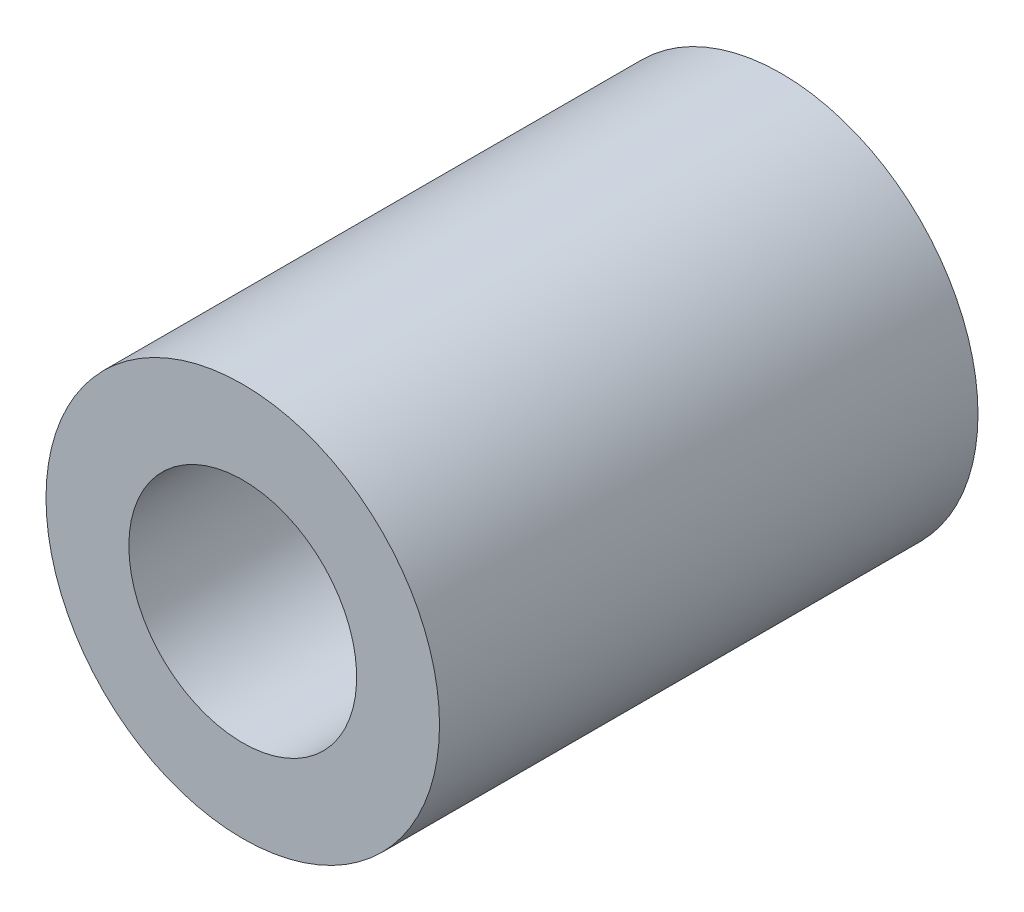
SolidWorks part; units mm, degrees
ref_plane "Alzado" through (0, 0, 0) normal (0, 0, 1) x (1, 0, 0)
ref_plane "Planta" through (0, 0, 0) normal (0, 1, 0) x (1, 0, 0)
ref_plane "Vista lateral" through (0, 0, 0) normal (1, 0, 0) x (0, 0, -1)
sketch "Croquis1" plane through (0, 0, 0) normal (0, 0, 1) x (1, 0, 0)
  circle A0 centre (0, 0) radius 4.75
  circle A1 centre (0, 0) radius 2.75
  dimension "D1" = 9.5
  dimension "D2" = 5.5
extrude "Saliente-Extruir1" add sketch "Croquis1" along normal blind 13
